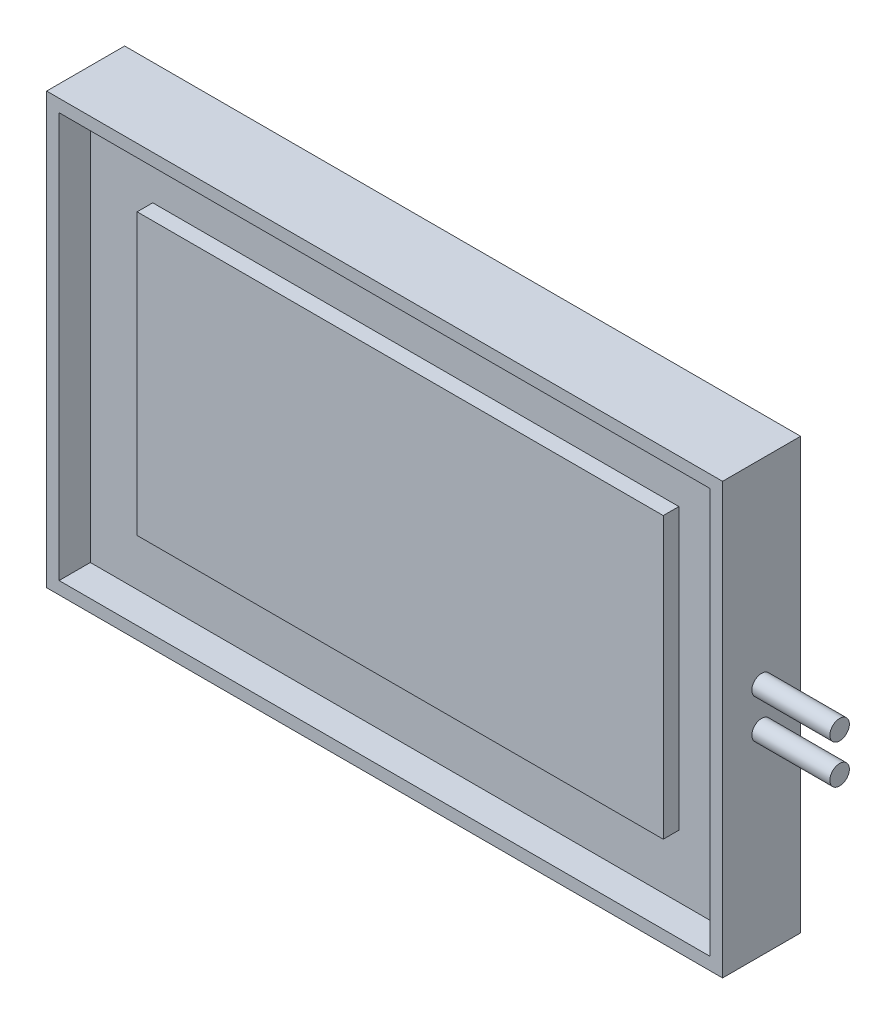
SolidWorks part; units mm, degrees
ref_plane "Front Plane" through (0, 0, 0) normal (0, 0, 1) x (1, 0, 0)
ref_plane "Top Plane" through (0, 0, 0) normal (0, 1, 0) x (1, 0, 0)
ref_plane "Right Plane" through (0, 0, 0) normal (1, 0, 0) x (0, 0, -1)
sketch "Sketch1" plane through (0, 0, 0) normal (0, 0, 1) x (1, 0, 0)
  line L1 (-83.7464, 33.5906) -> (-28.7464, 33.5906)
  line L2 (-83.7464, 33.5906) -> (-83.7464, -1.4094)
  line L3 (-83.7464, -1.4094) -> (-28.7464, -1.4094)
  line L4 (-28.7464, 33.5906) -> (-28.7464, -1.4094)
  dimension "D1" = 35
  dimension "D2" = 55
extrude "Boss-Extrude1" add sketch "Sketch1" along normal blind 6.35
sketch "Sketch2" plane through (-28.7464, 0, 0) normal (1, 0, 0) x (0, 0, -1)
  line L0 (-3.175, 17.6781) -> (-3.175, 14.5031) construction
  line L1 (-3.175, 16.0906) -> (0, 16.0906) construction
  line L2 (0, -1.4094) -> (0, 33.5906) construction
  line L3 (-6.35, 33.5906) -> (0, 33.5906) construction
  circle A0 centre (-3.175, 17.6781) radius 0.7938
  circle A1 centre (-3.175, 14.5031) radius 0.7938
  point P10 (-3.175, 33.5906)
  dimension "D2" = 1.5875
  dimension "D1" = 3.175
extrude "Boss-Extrude2" add sketch "Sketch2" along normal blind 6.35
sketch "Sketch3" plane through (0, 0, 6.35) normal (0, 0, 1) x (1, 0, 0)
  line L0 (-57.1839, 13.4906) -> (-55.3089, 13.4906) construction
  line L2 (-56.2464, 13.4906) -> (-56.2464, -1.4094) construction
  line L3 (-83.7464, -1.4094) -> (-28.7464, -1.4094) construction
  text T0 "FRONT" font "Century Gothic" height 5.08
  dimension "D1" = 1.875
  dimension "D2" = 14.9
extrude "Cut-Extrude1" [suppressed] cut sketch "Sketch3" against normal blind 0.254
sketch "Sketch4" plane through (0, 0, 0) normal (0, 0, -1) x (-1, 0, 0)
  line L0 (28.7464, 33.5906) -> (83.7464, -1.4094) construction
  circle A0 centre (56.2464, 16.0906) radius 1.5875
  dimension "D1" = 3.175
extrude "Cut-Extrude2" cut sketch "Sketch4" against normal blind 0.254
sketch "Sketch5" plane through (0, 0, 6.35) normal (0, 0, 1) x (1, 0, 0)
  line L0 (-29.7624, 32.5746) -> (-82.7304, 32.5746)
  line L1 (-82.7304, 32.5746) -> (-82.7304, -0.3934)
  line L2 (-82.7304, -0.3934) -> (-29.7624, -0.3934)
  line L3 (-29.7624, -0.3934) -> (-29.7624, 32.5746)
  line L4 (-83.7464, 33.5906) -> (-83.7464, -1.4094)
  line L5 (-83.7464, -1.4094) -> (-28.7464, -1.4094)
  line L6 (-28.7464, -1.4094) -> (-28.7464, 33.5906)
  line L7 (-28.7464, 33.5906) -> (-83.7464, 33.5906)
  line L8 (-83.7464, 33.5906) -> (-83.7464, -1.4094) construction
  line L9 (-83.7464, -1.4094) -> (-28.7464, -1.4094) construction
  line L10 (-28.7464, -1.4094) -> (-28.7464, 33.5906) construction
  line L11 (-28.7464, 33.5906) -> (-83.7464, 33.5906) construction
  dimension "D1" = 0
  dimension "D2" = 1.016
extrude "Cut-Extrude3" cut sketch "Sketch5" against normal blind 2.54
sketch "Sketch6" plane through (0, 0, 3.81) normal (0, 0, 1) x (1, 0, 0)
  line L0 (-34.8424, 27.4946) -> (-77.6504, 27.4946)
  line L1 (-77.6504, 27.4946) -> (-77.6504, 4.6866)
  line L2 (-77.6504, 4.6866) -> (-34.8424, 4.6866)
  line L3 (-34.8424, 4.6866) -> (-34.8424, 27.4946)
  line L4 (-29.7624, -0.3934) -> (-29.7624, 32.5746)
  line L5 (-29.7624, 32.5746) -> (-82.7304, 32.5746)
  line L6 (-82.7304, 32.5746) -> (-82.7304, -0.3934)
  line L7 (-82.7304, -0.3934) -> (-29.7624, -0.3934)
  line L8 (-29.7624, -0.3934) -> (-29.7624, 32.5746) construction
  line L9 (-29.7624, 32.5746) -> (-82.7304, 32.5746) construction
  line L10 (-82.7304, 32.5746) -> (-82.7304, -0.3934) construction
  line L11 (-82.7304, -0.3934) -> (-29.7624, -0.3934) construction
  dimension "D1" = 0
  dimension "D2" = 5.08
extrude "Boss-Extrude3" add sketch "Sketch6" along normal blind 1.27
ref_plane "Plane1" through (-56.2509, 0, 0) normal (-1, 0, 0) x (0, 0, 1)
sketch "Sketch7" plane through (-56.2509, 0, 0) normal (-1, 0, 0) x (0, 0, 1)
  line L0 (6.35, 166.0884) -> (6.35, -133.9116) construction
  line L2 (6.35, 16.0884) -> (156.35, 16.0884) construction
  circle A0 centre (156.35, 16.0884) radius 5
  circle A1 centre (151.2389, -22.7345) radius 5
  circle A2 centre (136.2538, -58.9116) radius 5
  circle A3 centre (112.416, -89.9776) radius 5
  circle A4 centre (81.35, -113.8154) radius 5
  circle A5 centre (45.1729, -128.8005) radius 5
  circle A6 centre (6.35, -133.9116) radius 5
  circle A7 centre (-32.4729, -128.8005) radius 5
  circle A8 centre (-68.65, -113.8154) radius 5
  circle A9 centre (-99.716, -89.9776) radius 5
  circle A10 centre (-123.5538, -58.9116) radius 5
  circle A11 centre (-138.5389, -22.7345) radius 5
  circle A12 centre (-143.65, 16.0884) radius 5
  circle A13 centre (-138.5389, 54.9112) radius 5
  circle A14 centre (-123.5538, 91.0884) radius 5
  circle A15 centre (-99.716, 122.1544) radius 5
  circle A16 centre (-68.65, 145.9922) radius 5
  circle A17 centre (-32.4729, 160.9773) radius 5
  circle A18 centre (6.35, 166.0884) radius 5
  circle A19 centre (45.1729, 160.9773) radius 5
  circle A20 centre (81.35, 145.9922) radius 5
  circle A21 centre (112.416, 122.1544) radius 5
  circle A22 centre (136.2538, 91.0884) radius 5
  circle A23 centre (151.2389, 54.9112) radius 5
  point P56 (6.35, 16.0884)
  dimension "D1" = 150
ref_plane "Plane4" through (0, 16.0906, 0) normal (0, -1, 0) x (-1, 0, 0)
sketch "Sketch8" plane through (0, 16.0906, 0) normal (0, -1, 0) x (-1, 0, 0)
  line L0 (56.2509, -6.35) -> (56.2509, -156.35) construction
  line L1 (206.2509, -6.35) -> (-93.7491, -6.35) construction
  circle A0 centre (56.2509, -156.35) radius 5
  circle A1 centre (17.428, -151.2389) radius 5
  circle A2 centre (-18.7491, -136.2538) radius 5
  circle A3 centre (-49.8151, -112.416) radius 5
  circle A4 centre (-73.6529, -81.35) radius 5
  circle A5 centre (-88.638, -45.1729) radius 5
  circle A6 centre (-93.7491, -6.35) radius 5
  circle A7 centre (-88.638, 32.4729) radius 5
  circle A8 centre (-73.6529, 68.65) radius 5
  circle A9 centre (-49.8151, 99.716) radius 5
  circle A10 centre (-18.7491, 123.5538) radius 5
  circle A11 centre (17.428, 138.5389) radius 5
  circle A12 centre (56.2509, 143.65) radius 5
  circle A13 centre (95.0737, 138.5389) radius 5
  circle A14 centre (131.2509, 123.5538) radius 5
  circle A15 centre (162.3169, 99.716) radius 5
  circle A16 centre (186.1547, 68.65) radius 5
  circle A17 centre (201.1398, 32.4729) radius 5
  circle A18 centre (206.2509, -6.35) radius 5
  circle A19 centre (201.1398, -45.1729) radius 5
  circle A20 centre (186.1547, -81.35) radius 5
  circle A21 centre (162.3169, -112.416) radius 5
  circle A22 centre (131.2509, -136.2538) radius 5
  circle A23 centre (95.0737, -151.2389) radius 5
  point P53 (56.2509, -6.35)
  dimension "D2" = 10
  dimension "D1" = 150
sketch "Sketch9" plane through (0, 0, 5.08) normal (0, 0, 1) x (1, 0, 0)
  line L4 (-34.8424, 4.6866) -> (-34.8424, 27.4946)
  line L5 (-34.8424, 27.4946) -> (-77.6504, 27.4946)
  line L6 (-77.6504, 27.4946) -> (-77.6504, 4.6866)
  line L7 (-77.6504, 4.6866) -> (-34.8424, 4.6866)
  line L8 (-34.8424, 4.6866) -> (-34.8424, 27.4946)
  line L9 (-34.8424, 27.4946) -> (-77.6504, 27.4946)
  line L10 (-77.6504, 27.4946) -> (-77.6504, 4.6866)
  line L11 (-77.6504, 4.6866) -> (-34.8424, 4.6866)
  circle A0 centre (-55.1352, 15.0575) radius 150
  dimension "D2" = 300
  dimension "D1" = 0
equation "\"D1@Sketch3\"=3.75/2"
equation "\"D2@Sketch1\"=\"Panel Width\""
equation "\"D1@Sketch1\"=\"Panel Height\""
equation "\"D2@Sketch3\"=3cm/2-.1"
equation "\"Panel Width\"= 5.5cm"
equation "\"Panel Height\"= 3.5cm"
equation "\"Panel Length\"= .6cm"
equation "\"Frame Thick\"= .125in"
equation "\"Overhang\"= .0675in"
